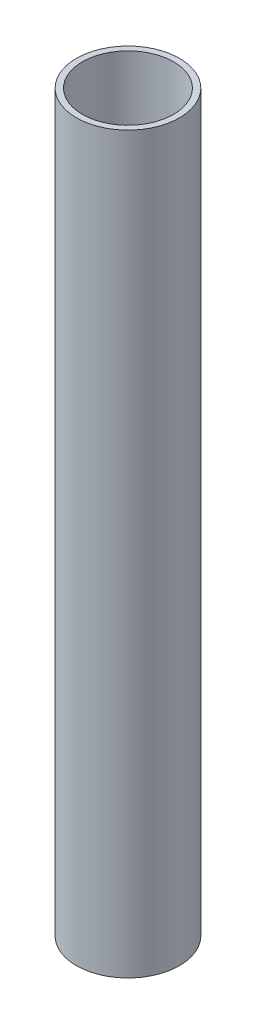
SolidWorks part; units mm, degrees
material "PVC Rigid"
ref_plane "Front Plane" through (0, 0, 0) normal (0, 0, 1) x (1, 0, 0)
ref_plane "Top Plane" through (0, 0, 0) normal (0, 1, 0) x (1, 0, 0)
ref_plane "Right Plane" through (0, 0, 0) normal (1, 0, 0) x (0, 0, -1)
sketch "Sketch1" plane through (0, 0, 0) normal (0, 1, 0) x (1, 0, 0)
  circle A0 centre (0, 0) radius 20
  circle A1 centre (0, 0) radius 17.7
  dimension "D1" = 40
  dimension "D2" = 2.3
extrude "Boss-Extrude1" add sketch "Sketch1" along normal blind 285
